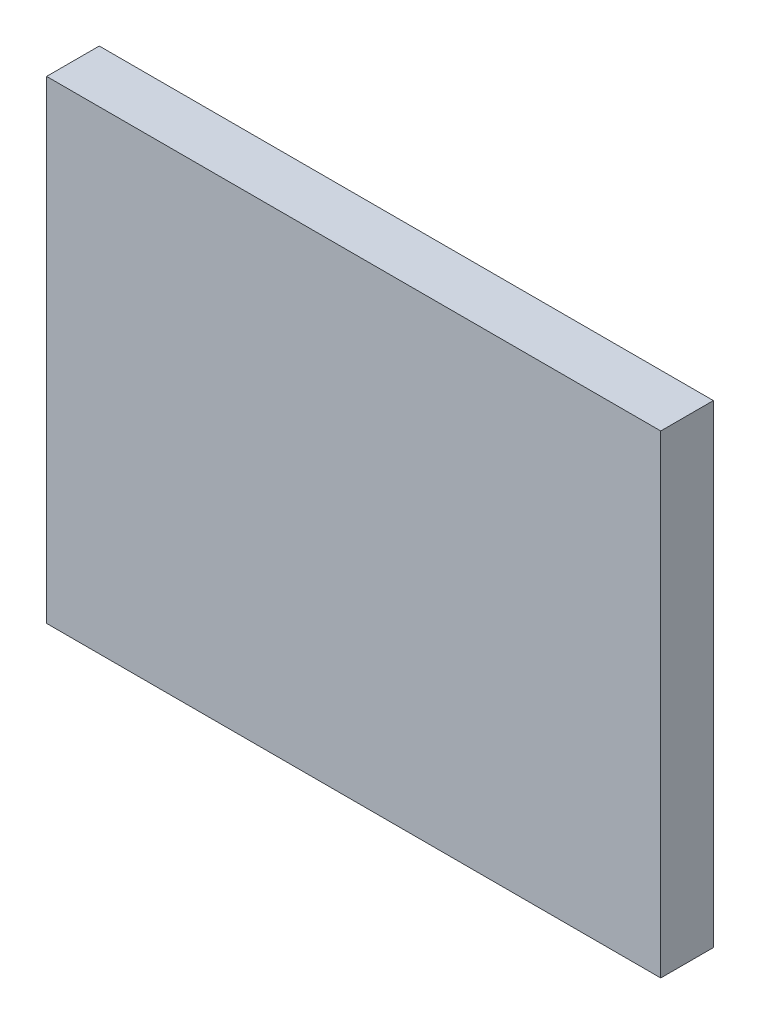
SolidWorks part; units mm, degrees
ref_plane "Plan de face" through (0, 0, 0) normal (0, 0, 1) x (1, 0, 0)
ref_plane "Plan de dessus" through (0, 0, 0) normal (0, 1, 0) x (1, 0, 0)
ref_plane "Plan de droite" through (0, 0, 0) normal (1, 0, 0) x (0, 0, -1)
sketch "Esquisse1" plane through (0, 0, 0) normal (0, 0, 1) x (1, 0, 0)
  line L0 (-17.5, 13.5) -> (17.5, -13.5) construction
  line L1 (-17.5, 13.5) -> (17.5, 13.5)
  line L2 (-17.5, 13.5) -> (-17.5, -13.5)
  line L3 (-17.5, -13.5) -> (17.5, -13.5)
  line L4 (17.5, 13.5) -> (17.5, -13.5)
  dimension "D1" = 35
  dimension "D2" = 27
extrude "Boss.-Extru.1" add sketch "Esquisse1" along normal blind 3
